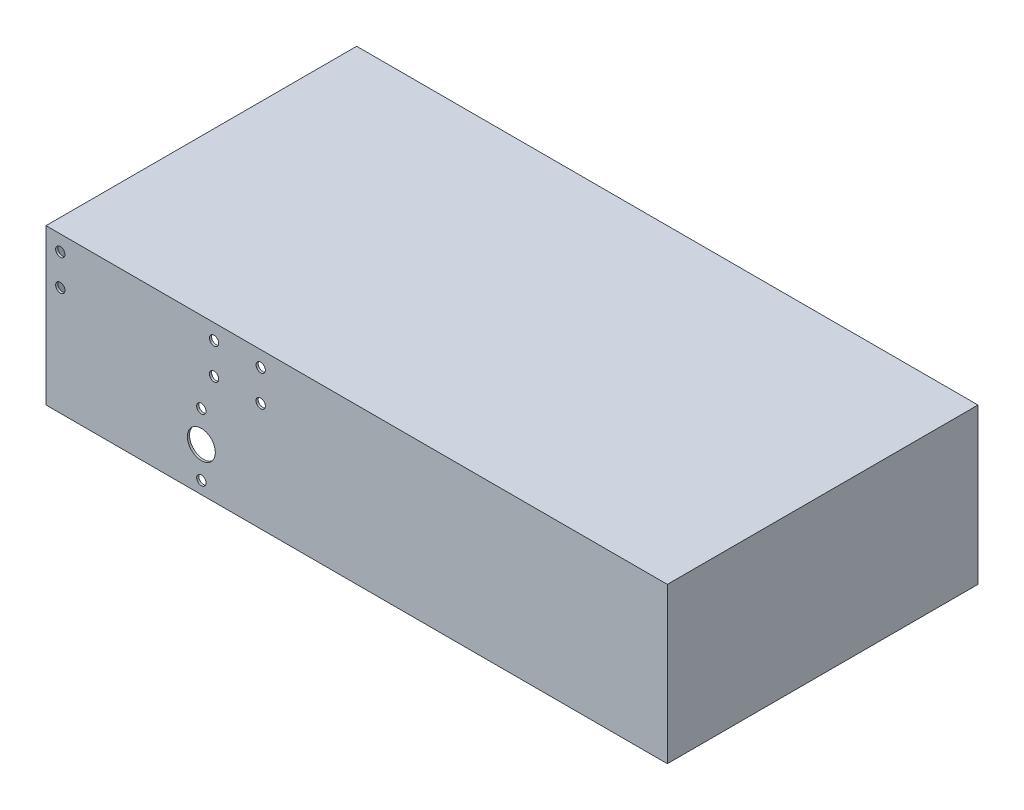
SolidWorks part; units mm, degrees
ref_plane "Front Plane" through (0, 0, 0) normal (0, 0, 1) x (1, 0, 0)
ref_plane "Top Plane" through (0, 0, 0) normal (0, 1, 0) x (1, 0, 0)
ref_plane "Right Plane" through (0, 0, 0) normal (1, 0, 0) x (0, 0, -1)
sketch "Sketch1" plane through (0, 0, 0) normal (0, 1, 0) x (1, 0, 0)
  line L1 (0, 50) -> (200, 50)
  line L2 (0, 50) -> (0, -50)
  line L3 (0, -50) -> (200, -50)
  line L4 (200, 50) -> (200, -50)
  point P4 (0, 0)
  dimension "D1" = 200
  dimension "D2" = 100
extrude "Boss-Extrude1" add sketch "Sketch1" along normal blind 50
sketch "Sketch2" plane through (0, 0, 50) normal (0, 0, 1) x (1, 0, 0)
  line L0 (0, 50) -> (0, 0) construction
  line L1 (50, 24) -> (50, 4) construction
  line L2 (0, 50) -> (200, 50) construction
  circle A0 centre (50, 14) radius 4.5
  circle A1 centre (50, 4) radius 1.5
  circle A2 centre (50, 24) radius 1.5
  point P0 (50, 14)
  point P9 (50, 14)
  dimension "D3" = 9
  dimension "D4" = 3
  dimension "D1" = 50
  dimension "D2" = 36
  dimension "D5" = 20
sketch "Sketch3" plane through (0, 0, 0) normal (0, -1, 0) x (1, 0, 0)
  line L0 (0.7, 49.3) -> (0.7, -49.3)
  line L1 (0.7, -49.3) -> (199.3, -49.3)
  line L2 (199.3, -49.3) -> (199.3, 49.3)
  line L3 (199.3, 49.3) -> (0.7, 49.3)
  line L4 (0, 50) -> (0, -50)
  line L5 (0, -50) -> (200, -50)
  line L6 (200, -50) -> (200, 50)
  line L7 (200, 50) -> (0, 50)
  line L8 (0, 50) -> (0, -50) construction
  line L9 (0, -50) -> (200, -50) construction
  line L10 (200, -50) -> (200, 50) construction
  line L11 (200, 50) -> (0, 50) construction
  dimension "D1" = 0
  dimension "D2" = 0.7
extrude "Cut-Extrude1" cut sketch "Sketch3" against normal offset from surface (49.3 mm away) 0.7 up to face at (100, 50, 0)
sketch "Sketch4" plane through (0, 0, 0) normal (0, -1, 0) x (1, 0, 0)
  line L0 (0.7, -49.3) -> (199.3, -49.3) construction
  line L1 (145, -49.3) -> (199.3, -49.3)
  line L2 (145, -49.3) -> (145, 49.3)
  line L3 (145, 49.3) -> (199.3, 49.3)
  line L4 (199.3, -49.3) -> (199.3, 49.3)
  line L5 (199.3, 49.3) -> (0.7, 49.3) construction
  line L6 (160, -47.9) -> (160, 49.3) construction
  line L7 (200, -50) -> (200, 50) construction
  line L8 (199.3, -49.3) -> (199.3, 49.3) construction
  circle A0 centre (160, 0.7) radius 11.43 construction
  point P12 (160, 0.7)
  point P18 (0, 0)
  dimension "D3" = 22.86
  dimension "D1" = 40
  dimension "D2" = 55
  dimension "D4" = 50
extrude "Boss-Extrude2" add sketch "Sketch4" against normal blind 0.7
extrude "Cut-Extrude2" cut sketch "Sketch2" against normal through all
sketch "Sketch6" plane through (0, 0, 50) normal (0, 0, 1) x (1, 0, 0)
  line L0 (4.6, 50) -> (4.6, 0) construction
  line L1 (0, 50) -> (200, 50) construction
  line L2 (200, 0) -> (0, 0) construction
  line L3 (0, 45) -> (200, 45) construction
  line L4 (0, 50) -> (0, 0) construction
  line L5 (200, 50) -> (200, 0) construction
  line L6 (0, 35) -> (200, 35) construction
  line L7 (54.1, 45) -> (54.1, 35) construction
  line L8 (69.1, 45) -> (69.1, 35) construction
  circle A0 centre (4.6, 45) radius 1.5
  circle A1 centre (4.6, 35) radius 1.5
  circle A2 centre (54.1, 45) radius 1.5
  circle A3 centre (54.1, 35) radius 1.5
  circle A4 centre (69.1, 45) radius 1.5
  circle A5 centre (69.1, 35) radius 1.5
  dimension "D1" = 3
  dimension "D3" = 5
  dimension "D4" = 10
  dimension "D5" = 4.6
  dimension "D6" = 15
  dimension "D7" = 54.1
extrude "Cut-Extrude3" cut sketch "Sketch6" against normal up to surface (0.7 mm away) up to face at (51.5, 4, 49.3)
sketch "Sketch7" plane through (0, 0, 0) normal (-1, 0, 0) x (0, 0, 1)
  line L0 (42, 50) -> (42, 0) construction
  line L1 (-50, 50) -> (50, 50) construction
  line L2 (-50, 0) -> (50, 0) construction
  circle A0 centre (42, 45) radius 1.5
  circle A1 centre (42, 35) radius 1.5
  dimension "D4" = 3
  dimension "D1" = 8
  dimension "D2" = 5
  dimension "D3" = 10
extrude "Cut-Extrude4" cut sketch "Sketch7" against normal up to surface (0.7 mm away) up to face at (0.7, 24.65, 0)
sketch "Sketch8" plane through (0, 0, 0) normal (0, -1, 0) x (1, 0, 0)
  line L0 (160, -47.9) -> (160, 49.3) construction
  circle A0 centre (160, 8.45) radius 1.21
  circle A1 centre (160, -7.05) radius 1.21
  point P6 (160, -6.053)
  dimension "D2" = 2.42
  dimension "D1" = 7.75
  dimension "D3" = 7.75
extrude "Cut-Extrude6" cut sketch "Sketch8" against normal up to next contours A1 | A0
